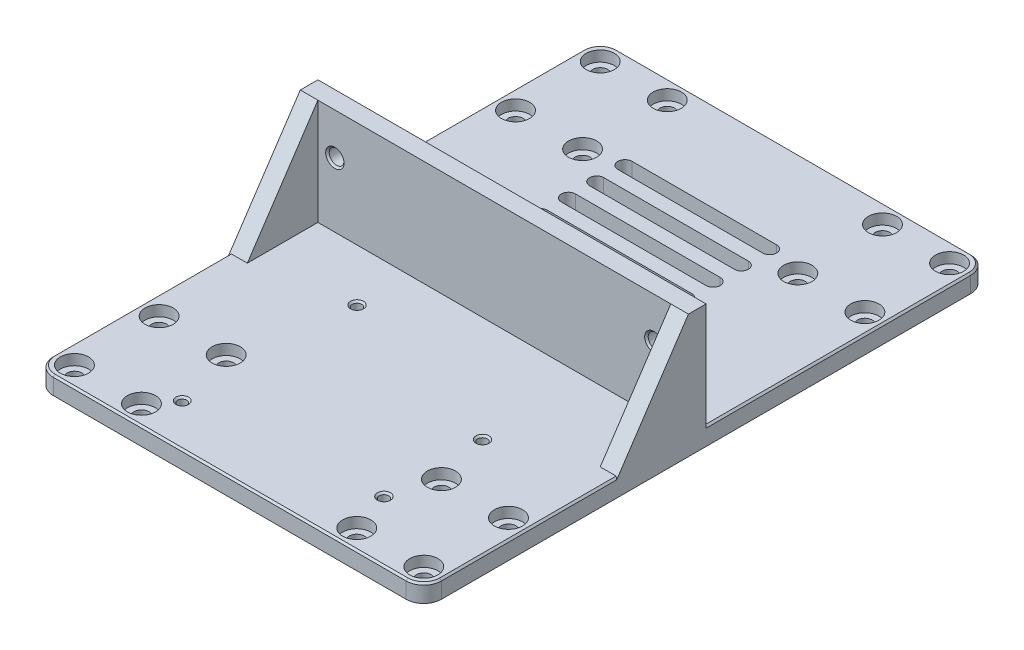
SolidWorks part; units mm, degrees
material "PET"
ref_plane "Přední rovina" through (0, 0, 0) normal (0, 0, 1) x (1, 0, 0)
ref_plane "Horní rovina" through (0, 0, 0) normal (0, 1, 0) x (1, 0, 0)
ref_plane "Pravá rovina" through (0, 0, 0) normal (1, 0, 0) x (0, 0, -1)
sketch "Skica2" plane through (0, 0, 0) normal (0, 1, 0) x (1, 0, 0)
  line L1 (0, 0) -> (110, 0)
  line L2 (0, 0) -> (0, 160)
  line L3 (0, 160) -> (110, 160)
  line L4 (110, 0) -> (110, 160)
  line L5 (0, 0) -> (110, 160) construction
  line L6 (0, 160) -> (110, 0) construction
  point P4 (55, 80)
  dimension "D1" = 110
  dimension "D2" = 160
extrude "Přidat vysunutím1" add sketch "Skica2" along normal blind 5
sketch "Skica3" plane through (0, 5, 0) normal (0, 1, 0) x (1, 0, 0)
  line L0 (0, 160) -> (0, 0) construction
  line L1 (0, 75) -> (110, 75)
  line L2 (0, 75) -> (0, 80)
  line L3 (0, 80) -> (110, 80)
  line L4 (110, 75) -> (110, 80)
  line L5 (0, 75) -> (110, 80) construction
  line L6 (0, 80) -> (110, 75) construction
  line L7 (110, 0) -> (110, 160) construction
  line L11 (110, 160) -> (0, 160) construction
  point P4 (55, 77.5)
  dimension "D1" = 5
  dimension "D2" = 80
extrude "Přidat vysunutím2" add sketch "Skica3" along normal blind 30
sketch "Skica4" plane through (0, 0, 0) normal (-1, 0, 0) x (0, 0, 1)
  line L0 (-75, 35) -> (-55, 5)
  line L1 (-75, 5) -> (0, 5) construction
  line L2 (-75, 35) -> (-75, 5) construction
  line L3 (-75, 35) -> (-75, 5)
  line L4 (-75, 5) -> (-55, 5)
  dimension "D1" = 20
extrude "Přidat vysunutím3" add sketch "Skica4" against normal blind 5
sketch "Skica5" plane through (110, 0, 0) normal (1, 0, 0) x (0, 0, -1)
  line L0 (75, 35) -> (55, 5)
  line L1 (55, 5) -> (75, 5)
  line L2 (75, 5) -> (75, 35)
extrude "Přidat vysunutím4" add sketch "Skica5" against normal blind 5
sketch "Skica6" plane through (0, 0, -80) normal (0, 0, -1) x (-1, 0, 0)
  line L0 (-110, 35) -> (-110, 5) construction
  line L1 (-110, 35) -> (0, 35) construction
  line L2 (-100.2, 23.25) -> (-9.8, 23.25) construction
  line L3 (0, 35) -> (0, 5) construction
  circle A0 centre (-100.2, 23.25) radius 2.1
  circle A1 centre (-9.8, 23.25) radius 2.1
  dimension "D1" = 9.8
  dimension "D3" = 4.2
  dimension "D4" = 4.2
  dimension "D2" = 11.75
  dimension "D5" = 9.8
extrude "Odebrat vysunutím1" cut sketch "Skica6" against normal up to surface (5 mm away) up to face at (55, 20, -75)
sketch "Skica8" plane through (0, 5, 0) normal (0, 1, 0) x (1, 0, 0)
  line L1 (0, 0) -> (30, 0) construction
  line L2 (0, 0) -> (0, 40) construction
  line L3 (0, 40) -> (30, 40) construction
  line L4 (30, 0) -> (30, 40) construction
  line L5 (0, 0) -> (110, 0) construction
  line L7 (110, 0) -> (80, 0) construction
  line L8 (110, 0) -> (110, 40) construction
  line L9 (110, 40) -> (80, 40) construction
  line L10 (80, 0) -> (80, 40) construction
  circle A0 centre (29.55, 12) radius 1.3
  circle A1 centre (30.82, 60.26) radius 1.35
  circle A2 centre (81.62, 17.09) radius 1.35
  circle A3 centre (81.62, 45.03) radius 1.35
  dimension "D4" = 52.07
  dimension "D5" = 2.6
  dimension "D6" = 2.7
  dimension "D7" = 2.7
  dimension "D8" = 2.7
  dimension "D1" = 40
  dimension "D2" = 30
  dimension "D3" = 30
  dimension "D9" = 1.27
  dimension "D10" = 48.26
  dimension "D11" = 5.09
  dimension "D12" = 27.94
  dimension "D13" = 29.55
  dimension "D14" = 12
extrude "Odebrat vysunutím3" cut sketch "Skica8" against normal up to surface (5 mm away) up to face at (55, 0, -80)
sketch "Skica9" plane through (0, 0, 0) normal (0, -1, 0) x (1, 0, 0)
  line L0 (0, -160) -> (0, 0) construction
  line L1 (5.5, -5.5) -> (24.5, -5.5) construction
  line L2 (5.5, -5.5) -> (5.5, -29.5) construction
  line L3 (5.5, -29.5) -> (24.5, -29.5) construction
  line L4 (24.5, -5.5) -> (24.5, -29.5) construction
  line L5 (5.5, -5.5) -> (24.5, -29.5) construction
  line L6 (5.5, -29.5) -> (24.5, -5.5) construction
  line L7 (0, 0) -> (110, 0) construction
  line L8 (55, 0) -> (55, -43.8272) construction
  line L9 (104.5, -29.5) -> (85.5, -5.5) construction
  line L10 (104.5, -5.5) -> (85.5, -29.5) construction
  line L11 (85.5, -5.5) -> (85.5, -29.5) construction
  line L12 (104.5, -29.5) -> (85.5, -29.5) construction
  line L13 (104.5, -5.5) -> (104.5, -29.5) construction
  line L14 (104.5, -5.5) -> (85.5, -5.5) construction
  line L15 (0, -80) -> (110, -80) construction
  line L16 (110, 0) -> (110, -160) construction
  line L17 (104.5, -154.5) -> (85.5, -154.5) construction
  line L18 (104.5, -154.5) -> (104.5, -130.5) construction
  line L19 (104.5, -130.5) -> (85.5, -130.5) construction
  line L20 (85.5, -154.5) -> (85.5, -130.5) construction
  line L21 (104.5, -154.5) -> (85.5, -130.5) construction
  line L22 (104.5, -130.5) -> (85.5, -154.5) construction
  line L23 (5.5, -130.5) -> (24.5, -154.5) construction
  line L24 (5.5, -154.5) -> (24.5, -130.5) construction
  line L25 (24.5, -154.5) -> (24.5, -130.5) construction
  line L26 (5.5, -130.5) -> (24.5, -130.5) construction
  line L27 (5.5, -154.5) -> (5.5, -130.5) construction
  line L28 (5.5, -154.5) -> (24.5, -154.5) construction
  circle A0 centre (5.5, -5.5) radius 2.1
  circle A1 centre (24.5, -5.5) radius 2.1
  circle A2 centre (5.5, -29.5) radius 2.1
  circle A3 centre (24.5, -29.5) radius 2.1
  circle A4 centre (85.5, -29.5) radius 2.1
  circle A5 centre (104.5, -29.5) radius 2.1
  circle A6 centre (85.5, -5.5) radius 2.1
  circle A7 centre (104.5, -5.5) radius 2.1
  circle A8 centre (104.5, -154.5) radius 2.1
  circle A9 centre (85.5, -154.5) radius 2.1
  circle A10 centre (104.5, -130.5) radius 2.1
  circle A11 centre (85.5, -130.5) radius 2.1
  circle A12 centre (24.5, -130.5) radius 2.1
  circle A13 centre (5.5, -130.5) radius 2.1
  circle A14 centre (24.5, -154.5) radius 2.1
  circle A15 centre (5.5, -154.5) radius 2.1
  point P4 (15, -17.5)
  point P23 (95, -17.5)
  point P44 (95, -142.5)
  point P45 (15, -142.5)
  dimension "D5" = 4.2
  dimension "D6" = 4.2
  dimension "D7" = 4.2
  dimension "D8" = 4.2
  dimension "D1" = 24
  dimension "D2" = 19
  dimension "D3" = 5.5
  dimension "D4" = 5.5
extrude "Odebrat vysunutím4" cut sketch "Skica9" against normal up to surface (5 mm away) up to face at (30.82, 5, -58.91)
sketch "Skica10" plane through (0, 5, 0) normal (0, 1, 0) x (1, 0, 0)
  line L0 (55, 160) -> (55, 0) construction
  line L1 (110, 160) -> (0, 160) construction
  line L2 (0, 0) -> (110, 0) construction
  line L3 (0, 80) -> (110, 80) construction
  line L6 (0, 55) -> (0, 0) construction
  line L7 (110, 0) -> (110, 55) construction
  circle A0 centre (5.5, 154.5) radius 4
  circle A1 centre (24.5, 154.5) radius 4
  circle A2 centre (5.5, 130.5) radius 4
  circle A3 centre (24.5, 130.5) radius 4
  circle A4 centre (85.5, 130.5) radius 4
  circle A5 centre (104.5, 130.5) radius 4
  circle A6 centre (85.5, 154.5) radius 4
  circle A7 centre (104.5, 154.5) radius 4
  circle A8 centre (104.5, 5.5) radius 4
  circle A9 centre (85.5, 5.5) radius 4
  circle A10 centre (104.5, 29.5) radius 4
  circle A11 centre (85.5, 29.5) radius 4
  circle A12 centre (24.5, 29.5) radius 4
  circle A13 centre (5.5, 29.5) radius 4
  circle A14 centre (24.5, 5.5) radius 4
  circle A15 centre (5.5, 5.5) radius 4
  dimension "D1" = 8
  dimension "D2" = 8
  dimension "D3" = 8
  dimension "D4" = 8
  dimension "D5" = 80
extrude "Odebrat vysunutím5" cut sketch "Skica10" against normal blind 3
fillet "Zaoblit1" radius 5 4 edges at (110, 2.5, 0) (110, 2.5, -160) (0, 2.5, -160) (0, 2.5, 0)
chamfer "Zkosení3" distance 0.5 angle 45 10 edges at (0, 5, -30) (1.4645, 5, -1.4645) (55, 5, 0) (108.5355, 5, -1.4645) (110, 5, -30) (0, 5, -117.5) (1.4645, 5, -158.5355) (55, 5, -160) (108.5355, 5, -158.5355) (110, 5, -117.5)
chamfer "Zkosení6" distance 0.5 angle 45 4 edges at (7.7, 23.25, -80) (7.7, 23.25, -75) (98.1, 23.25, -75) (98.1, 23.25, -80)
sketch "Skica11" plane through (0, 5, 0) normal (0, 1, 0) x (1, 0, 0)
  line L0 (55, 160) -> (55, 80) construction
  line L1 (5, 160) -> (105, 160) construction
  line L2 (110, 80) -> (0, 80) construction
  line L3 (34.5, 132.5) -> (75.5, 132.5) construction
  line L4 (34.5, 134.5) -> (75.5, 134.5)
  line L5 (34.5, 130.5) -> (75.5, 130.5)
  line L6 (34.5, 124.5) -> (75.5, 124.5) construction
  line L7 (34.5, 126.5) -> (75.5, 126.5)
  line L8 (34.5, 122.5) -> (75.5, 122.5)
  line L9 (34.5, 116.5) -> (75.5, 116.5) construction
  line L10 (34.5, 118.5) -> (75.5, 118.5)
  line L11 (34.5, 114.5) -> (75.5, 114.5)
  line L12 (34.5, 108.5) -> (75.5, 108.5) construction
  line L13 (34.5, 110.5) -> (75.5, 110.5)
  line L14 (34.5, 106.5) -> (75.5, 106.5)
  line L15 (34.5, 100.5) -> (75.5, 100.5) construction
  line L16 (34.5, 102.5) -> (75.5, 102.5)
  line L17 (34.5, 98.5) -> (75.5, 98.5)
  line L18 (109.5, 80) -> (0.5, 80) construction
  line L21 (87.7562, 80) -> (22.2438, 80) construction
  line L22 (87.7562, 80) -> (87.7562, 137) construction
  line L23 (87.7562, 137) -> (22.2438, 137) construction
  line L24 (22.2438, 80) -> (22.2438, 137) construction
  line L25 (87.7562, 80) -> (22.2438, 137) construction
  line L26 (87.7562, 137) -> (22.2438, 80) construction
  line L27 (34.5, 92.5) -> (75.5, 92.5) construction
  line L28 (34.5, 94.5) -> (75.5, 94.5)
  line L29 (34.5, 90.5) -> (75.5, 90.5)
  line L30 (34.5, 84.5) -> (75.5, 84.5) construction
  line L31 (34.5, 86.5) -> (75.5, 86.5)
  line L32 (34.5, 82.5) -> (75.5, 82.5)
  arc A0 (34.5, 134.5) -> (34.5, 130.5) centre (34.5, 132.5) ccw
  arc A1 (75.5, 130.5) -> (75.5, 134.5) centre (75.5, 132.5) ccw
  arc A2 (34.5, 126.5) -> (34.5, 122.5) centre (34.5, 124.5) ccw
  arc A3 (75.5, 122.5) -> (75.5, 126.5) centre (75.5, 124.5) ccw
  arc A4 (34.5, 118.5) -> (34.5, 114.5) centre (34.5, 116.5) ccw
  arc A5 (75.5, 114.5) -> (75.5, 118.5) centre (75.5, 116.5) ccw
  arc A6 (34.5, 110.5) -> (34.5, 106.5) centre (34.5, 108.5) ccw
  arc A7 (75.5, 106.5) -> (75.5, 110.5) centre (75.5, 108.5) ccw
  arc A8 (34.5, 102.5) -> (34.5, 98.5) centre (34.5, 100.5) ccw
  arc A9 (75.5, 98.5) -> (75.5, 102.5) centre (75.5, 100.5) ccw
  arc A10 (34.5, 94.5) -> (34.5, 90.5) centre (34.5, 92.5) ccw
  arc A11 (75.5, 90.5) -> (75.5, 94.5) centre (75.5, 92.5) ccw
  arc A12 (34.5, 86.5) -> (34.5, 82.5) centre (34.5, 84.5) ccw
  arc A13 (75.5, 82.5) -> (75.5, 86.5) centre (75.5, 84.5) ccw
  point P8 (55, 132.5)
  point P17 (55, 124.5)
  point P24 (55, 116.5)
  point P31 (55, 108.5)
  point P38 (55, 100.5)
  point P45 (55, 108.5)
  point P53 (55, 92.5)
  point P63 (55, 84.5)
  dimension "D2" = 45
  dimension "D1" = 4
  dimension "D3" = 57
  dimension "D5" = 4
  dimension "D6" = 5
  dimension "D4" = 7
extrude "Odebrat vysunutím6" cut sketch "Skica11" against normal up to surface (5 mm away) up to face at (104.5, 0, -27.4)
chamfer "Zkosení7" distance 0.5 angle 45 4 edges at (81.62, 5, -43.68) (81.62, 5, -15.74) (29.55, 5, -10.7) (30.82, 5, -58.91)
